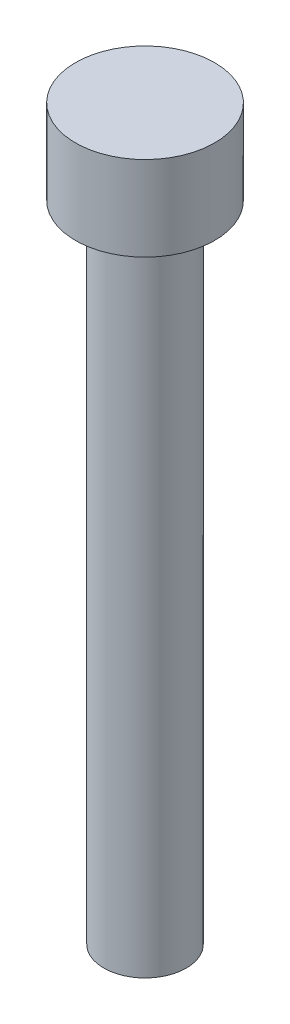
SolidWorks part; units mm, degrees
ref_plane "Front Plane" through (0, 0, 0) normal (0, 0, 1) x (1, 0, 0)
ref_plane "Top Plane" through (0, 0, 0) normal (0, 1, 0) x (1, 0, 0)
ref_plane "Right Plane" through (0, 0, 0) normal (1, 0, 0) x (0, 0, -1)
sketch "Sketch1" plane through (0, 0, 0) normal (0, 0, 1) x (1, 0, 0)
  line L0 (0, 0) -> (0, 35.9156)
  line L1 (0, 35.9156) -> (3.429, 35.9156)
  line L2 (3.429, 35.9156) -> (3.429, 31.75)
  line L3 (3.429, 31.75) -> (2.032, 31.75)
  line L4 (2.032, 31.75) -> (2.032, 0)
  line L5 (2.032, 0) -> (0, 0)
  dimension "D1" = 2.032
  dimension "D2" = 31.75
  dimension "D3" = 4.1656
  dimension "D4" = 3.429
revolve "Revolve1" add sketch "Sketch1" angle 360 about L0
